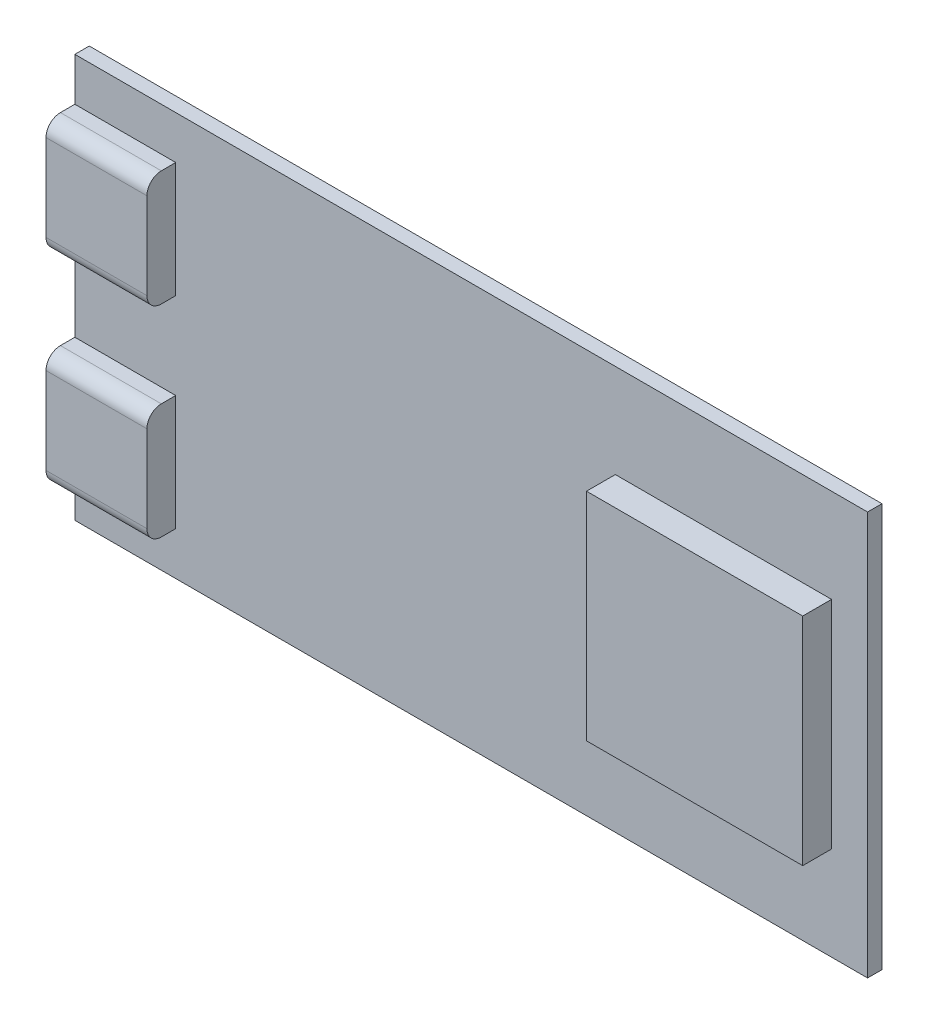
SolidWorks part; units mm, degrees
ref_plane "前视基准面" through (0, 0, 0) normal (0, 0, 1) x (1, 0, 0)
ref_plane "上视基准面" through (0, 0, 0) normal (0, 1, 0) x (1, 0, 0)
ref_plane "右视基准面" through (0, 0, 0) normal (1, 0, 0) x (0, 0, -1)
other "Configuration Table"
sketch "草图1" plane through (0, 0, 0) normal (0, 0, 1) x (1, 0, 0)
  line L1 (27.5, -14) -> (-27.5, -14)
  line L2 (27.5, -14) -> (27.5, 14)
  line L3 (27.5, 14) -> (-27.5, 14)
  line L4 (-27.5, -14) -> (-27.5, 14)
  line L5 (27.5, -14) -> (-27.5, 14) construction
  line L6 (27.5, 14) -> (-27.5, -14) construction
  point P0 (0, 0)
  dimension "D1" = 55
  dimension "D2" = 28
extrude "凸台-拉伸1" add sketch "草图1" along normal blind 1
sketch "草图2" plane through (0, 0, 1) normal (0, 0, 1) x (1, 0, 0)
  line L0 (-27.5, -14) -> (27.5, -14) construction
  line L1 (25, -7.5) -> (10, -7.5)
  line L2 (25, -7.5) -> (25, 7.5)
  line L3 (25, 7.5) -> (10, 7.5)
  line L4 (10, -7.5) -> (10, 7.5)
  line L5 (25, -7.5) -> (10, 7.5) construction
  line L6 (25, 7.5) -> (10, -7.5) construction
  line L7 (27.5, -14) -> (27.5, 14) construction
  point P0 (17.5, 0)
  dimension "D1" = 15
  dimension "D2" = 15
  dimension "D3" = 14
  dimension "D4" = 10
extrude "凸台-拉伸2" add sketch "草图2" along normal blind 2
sketch "草图3" plane through (0, 0, 1) normal (0, 0, 1) x (1, 0, 0)
  line L0 (-27.5, 0) -> (27.5, 0) construction
  line L1 (-27.5, 14) -> (-27.5, -14) construction
  line L2 (27.5, -14) -> (27.5, 14) construction
  line L3 (-20.5, -11) -> (-27.5, -11)
  line L4 (-20.5, 3) -> (-27.5, 3)
  line L5 (-20.5, 3) -> (-20.5, 11)
  line L6 (-20.5, 11) -> (-27.5, 11)
  line L7 (-27.5, 3) -> (-27.5, 11)
  line L8 (-20.5, 3) -> (-27.5, 11) construction
  line L9 (-20.5, 11) -> (-27.5, 3) construction
  line L10 (-27.5, -3) -> (-27.5, -11)
  line L11 (-20.5, -3) -> (-27.5, -3)
  line L12 (-20.5, -3) -> (-20.5, -11)
  point P6 (-24, 7)
  dimension "D1" = 7
  dimension "D2" = 8
  dimension "D3" = 7
extrude "凸台-拉伸3" add sketch "草图3" along normal blind 2
fillet "圆角1" radius 1 4 edges at (-24, -11, 3) (-24, -3, 3) (-24, 3, 3) (-24, 11, 3)
